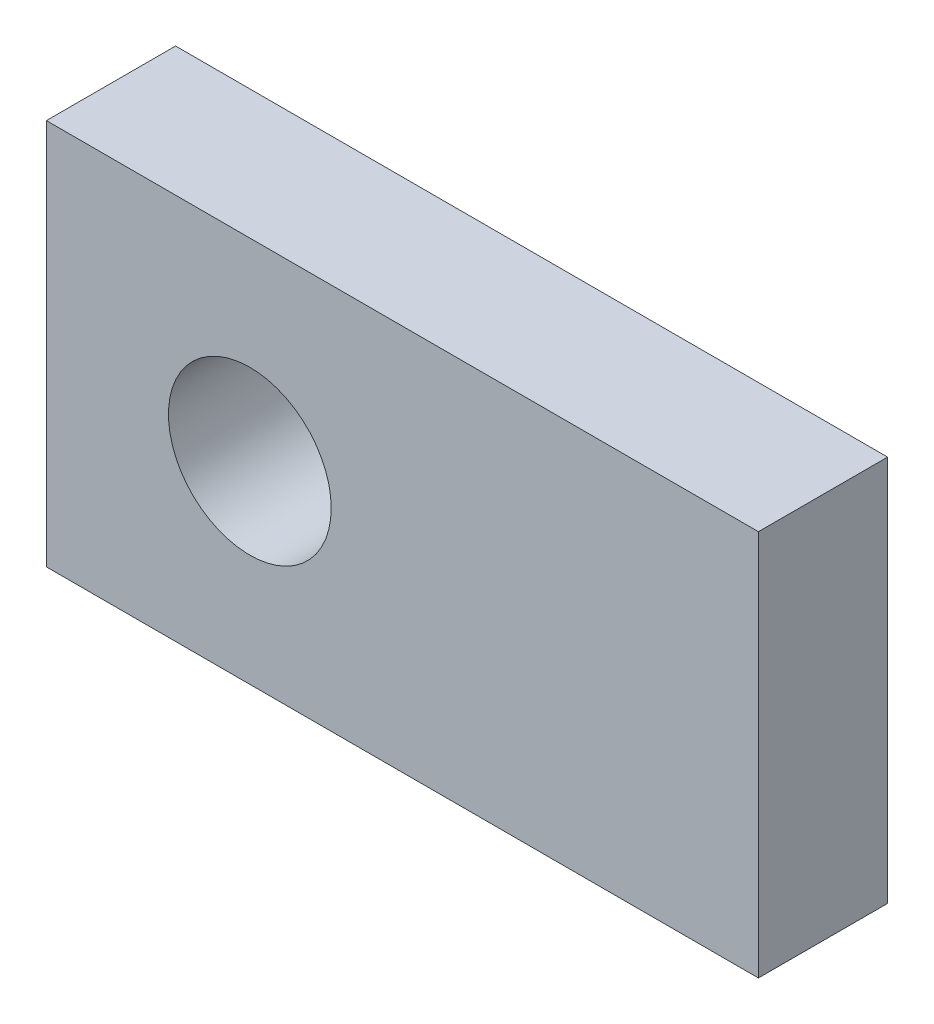
SolidWorks part; units mm, degrees
ref_plane "Piano frontale" through (0, 0, 0) normal (0, 0, 1) x (1, 0, 0)
ref_plane "Piano superiore" through (0, 0, 0) normal (0, 1, 0) x (1, 0, 0)
ref_plane "Piano destro" through (0, 0, 0) normal (1, 0, 0) x (0, 0, -1)
sketch "Schizzo1" plane through (0, 0, 0) normal (0, 0, 1) x (1, 0, 0)
  line L1 (17.5, -9.5) -> (-17.5, -9.5)
  line L2 (17.5, -9.5) -> (17.5, 9.5)
  line L3 (17.5, 9.5) -> (-17.5, 9.5)
  line L4 (-17.5, -9.5) -> (-17.5, 9.5)
  line L5 (17.5, -9.5) -> (-17.5, 9.5) construction
  line L6 (17.5, 9.5) -> (-17.5, -9.5) construction
  circle A0 centre (-7.5, 0) radius 4
  point P0 (0, 0)
  point P8 (-17.5, 0)
  point P11 (-17.5, 1.0739)
  dimension "D3" = 8
  dimension "D1" = 35
  dimension "D2" = 19
  dimension "D4" = 10
  dimension "D5" = 9.5
extrude "Estrusione-Estrusione1" add sketch "Schizzo1" along normal blind 6.35
